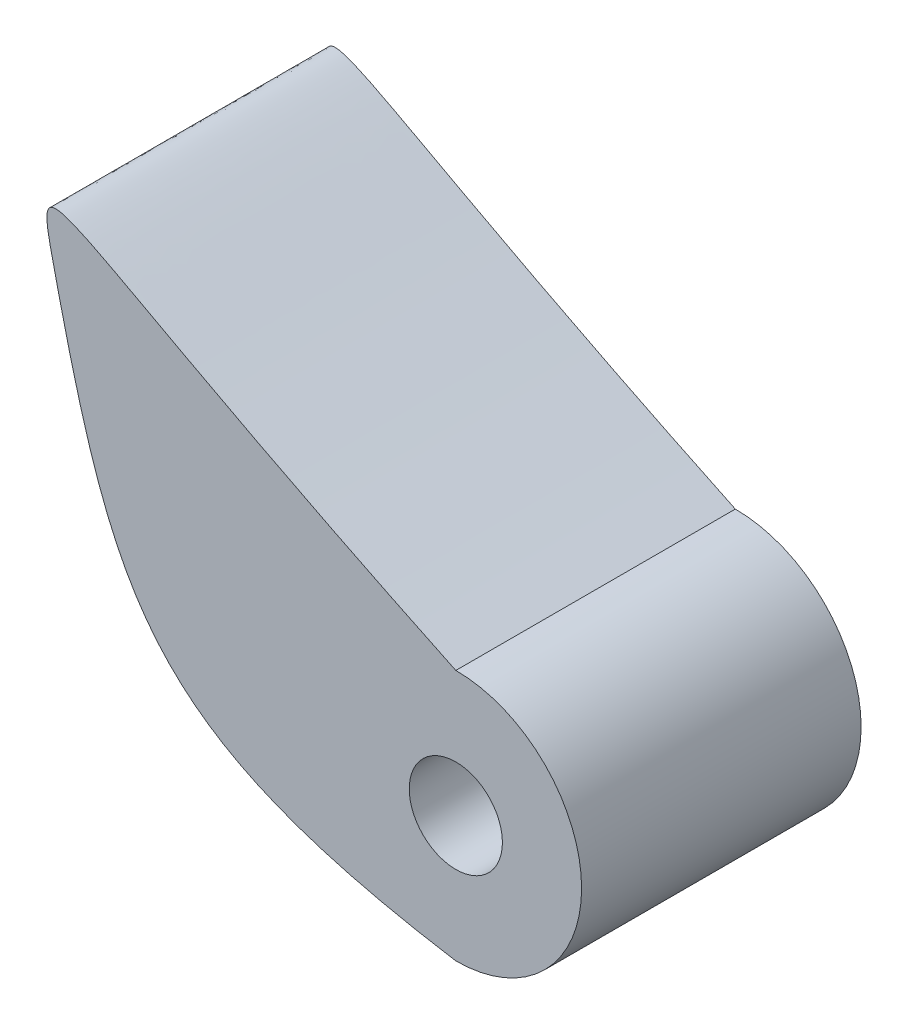
SolidWorks part; units mm, degrees
ref_plane "Plan de face" through (0, 0, 0) normal (0, 0, 1) x (1, 0, 0)
ref_plane "Plan de dessus" through (0, 0, 0) normal (0, 1, 0) x (1, 0, 0)
ref_plane "Plan de droite" through (0, 0, 0) normal (1, 0, 0) x (0, 0, -1)
sketch "Esquisse1" plane through (0, 0, 0) normal (0, 0, 1) x (1, 0, 0)
  circle A0 centre (0, 0) radius 2.5
  circle A1 centre (0, 0) radius 6.75
  spline S0 degree 3 poles (0, -6.75) (-12.8411, -4.6648) (-18.2184, 0.1016) (-23.1139, 21.4668) (-22.1621, 17.2865) (0, 6.75) knots 0 0 0 0 0.428894 0.581534 1 1 1 1
  point P6 (-17.0081, 0)
  point P8 (0, 0)
  point P10 (0, 0)
  point P11 (-21.5448, 14.6172)
  point P12 (-15.1778, 0.6722)
  point P13 (-19.3964, 6.5314)
  dimension "D1" = 5
  dimension "D2" = 13.5
extrude "Boss.-Extru.2" add sketch "Esquisse1" against normal blind 15 contours S0 A1 A0 | S0 A1
